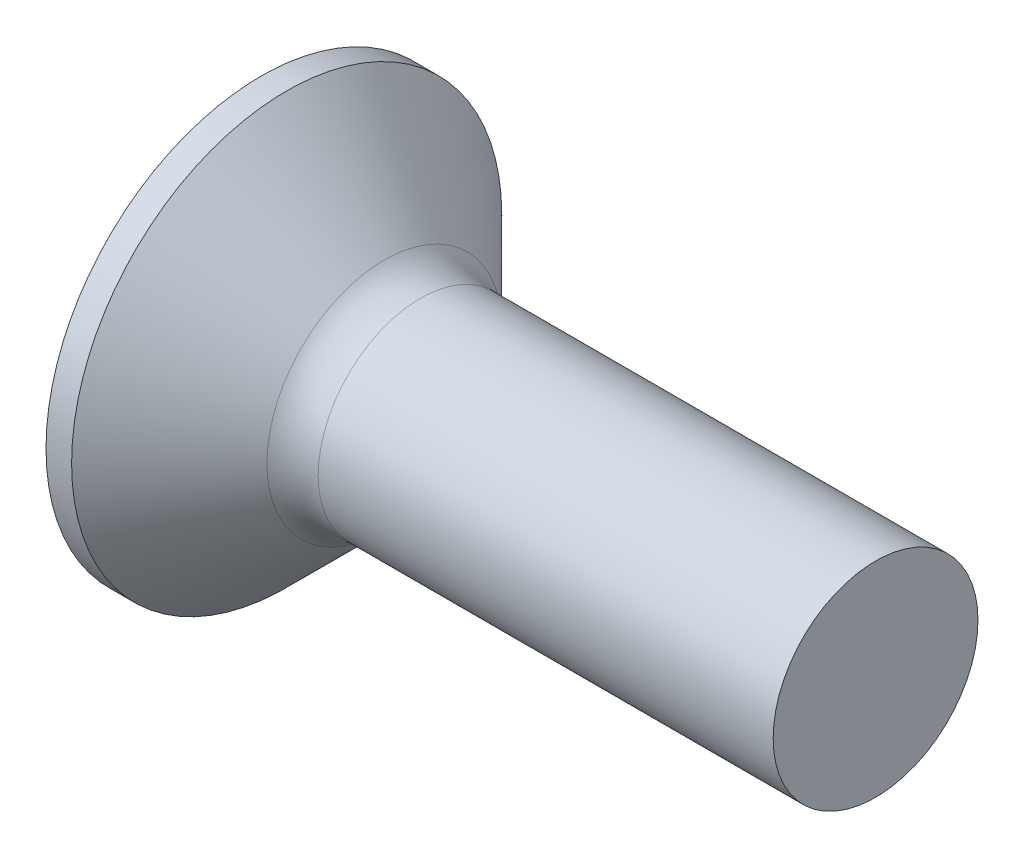
SolidWorks part; units mm, degrees
revolve "Base-Revolve" add sketch "BodySke"
sketch "BodySke" plane through (0, 0, 0) normal (0, 0, 1) x (1, 0, 0)
  line L0 (0, 0) -> (0, 4.2)
  line L1 (0, 4.2) -> (0.5, 4.2)
  line L2 (2.7, 2) -> (12, 2)
  line L3 (12, 2) -> (12, 0)
  line L4 (12, 0) -> (0, 0)
  line L5 (-6.35, 0) -> (82.55, 0) construction
  line L6 (2.7, -2) -> (12, -2) construction
  line L7 (0.5, -4.2) -> (2.7, -2) construction
  line L8 (0.5, 4.2) -> (2.7, 2)
  line L9 (0, -4.2) -> (0.5, -4.2) construction
  line L10 (3.4, 3.5875) -> (3.4, -5.9375) construction
  line L11 (0, 6.35) -> (0, -3.175) construction
  dimension "Diameter" = 4
  dimension "Length" = 12
  dimension "Head_ht" = 2.7
  dimension "Head_dia" = 8.4
  dimension "Head_ang" = 90
  dimension "D6" = 0.5
  dimension "Advance" = 0.7
  dimension "Thread_nom" = 12
cosmetic thread "ThreadCosmetic" [suppressed]
fillet "Fillet1" radius 1 1 edges at (2.7, 0, 2)
material "AISI 4340 Steel, annealed"
ref_plane "Plane1" through (0, 0, 0) normal (0, 0, 1) x (1, 0, 0)
ref_plane "Plane2" through (0, 0, 0) normal (0, 1, 0) x (1, 0, 0)
ref_plane "Plane3" through (0, 0, 0) normal (1, 0, 0) x (0, 0, -1)
other "Configuration Table"
sketch "Sketch3" plane through (0, 0, 0) normal (-1, 0, 0) x (0, 0, 1)
  line L0 (-0.515, 2.2) -> (0.515, 2.2)
  line L1 (0.515, 2.2) -> (0.515, -2.2)
  line L2 (0.515, -2.2) -> (-0.515, -2.2)
  line L3 (-0.515, -2.2) -> (-0.515, 2.2)
  dimension "Cross_dia" = 4.4
  dimension "Cross_width" = 1.03
  dimension "D1" = 2.2
  dimension "D2" = 0.515
ref_plane "Plane4" through (2.51, 0, 0) normal (-1, 0, 0) x (0, 0, 1)
sketch "Sketch4" plane through (2.51, 0, 0) normal (-1, 0, 0) x (0, 0, 1)
  line L0 (-0.515, 0.9486) -> (0.515, 0.9486)
  line L3 (0.515, 0.9486) -> (0.515, -0.9486)
  line L4 (0.515, -0.9486) -> (-0.515, -0.9486)
  line L5 (-0.515, -0.9486) -> (-0.515, 0.9486)
  dimension "D2" = 1.8971
  dimension "D1" = 1.03
  dimension "D4" = 0.9486
  dimension "D3" = 0.515
loft "Recess" cut profiles "Sketch3", "Sketch4"
pattern_circular "RecPat" count 2 every 90 about axis through (0, 0, 0) along (1, 0, 0) of "Recess"
sketch "RecCorSke" plane through (0, 0, 0) normal (0, 0, 1) x (1, 0, 0)
  line L0 (-3.175, 0) -> (15.875, 0) construction
  line L2 (0, 0) -> (0, 1.0265)
  line L3 (0, 1.0265) -> (2.51, 0.851)
  line L4 (2.51, 0.851) -> (2.7865, 0)
  line L5 (2.7865, 0) -> (0, 0)
  dimension "Diameter" = 1.702
  dimension "Depth" = 2.51
  dimension "Draft_angle" = 4
  dimension "Bottom_angle" = 18
revolve "RecessCore" cut sketch "RecCorSke" angle 360 about L0
sketch "ThdSchSke" plane through (0, 0, 0) normal (0, 0, 1) x (1, 0, 0)
  line L0 (3.4, -1.61) -> (3.1269, -2)
  line L1 (3.4, -1.61) -> (3.6731, -2)
  line L2 (3.6731, -2) -> (3.6731, -2.5)
  line L3 (-3.175, 0) -> (5.1513, 0) construction
  line L5 (3.6731, -2.5) -> (3.1269, -2.5)
  line L6 (3.1269, -2.5) -> (3.1269, -2)
  line L7 (0, 4.2) -> (0, -4.2) construction
  dimension "Diameter" = 4
  dimension "Thread_minor" = 3.22
  dimension "Start" = 3.4
revolve "ThreadSchematic" [suppressed] cut sketch "ThdSchSke" angle 360 about L3
pattern_linear "ThdSchPat" [suppressed]
equation "\"D1@Sketch3\" = \"Cross_dia@Sketch3\" / 2"
equation "\"D2@Sketch3\" = \"Cross_width@Sketch3\" / 2"
equation "\"Depth@RecCorSke\" = \"Cross_depth@Plane4\""
equation "\"D1@Sketch4\" = \"Cross_width@Sketch3\""
equation "\"D2@Sketch4\" = \"Cross_dia@Sketch3\" - 2.0 * \"Cross_depth@Plane4\" * tan(26.5  * 0.017453292)"
equation "\"D3@Sketch4\" = \"D1@Sketch4\" / 2"
equation "\"D4@Sketch4\" = \"D2@Sketch4\" / 2"
equation "\"Thread_length@ThreadCosmetic\" = ((sgn( (\"Length@BodySke\" - \"Advance@BodySke\" * 1.0 - \"Head_ht@BodySke\" ) - \"Thread_nom@BodySke\" )-1)*( (\"Length@BodySke\" - \"Advance@BodySke\" * 1.0 - \"Head_ht@BodySke\" ) - \"Thread_nom@BodySke\" ))/-2+ \"Thread_nom@BodySke\""
equation "\"Thread_minor@ThdSchSke\" = \"Thread_minor@ThreadCosmetic\""
equation "\"Diameter@ThdSchSke\" = \"Diameter@BodySke\""
equation "\"Overcut@ThdSchSke\" = \"Diameter@BodySke\" * 1.25"
equation "\"Start@ThdSchSke\" = 0.000001 + \"Length@BodySke\" - \"Thread_length@ThreadCosmetic\"  '---Countersunk---"
equation "\"Num_threads@ThdSchPat\" = int( \"Thread_length@ThreadCosmetic\" / \"Advance@BodySke\" + 0.999 )  + 1"
equation "\"Advance@ThdSchPat\" = \"Thread_length@ThreadCosmetic\" /  (\"Num_threads@ThdSchPat\" - 1) 'relax it"
